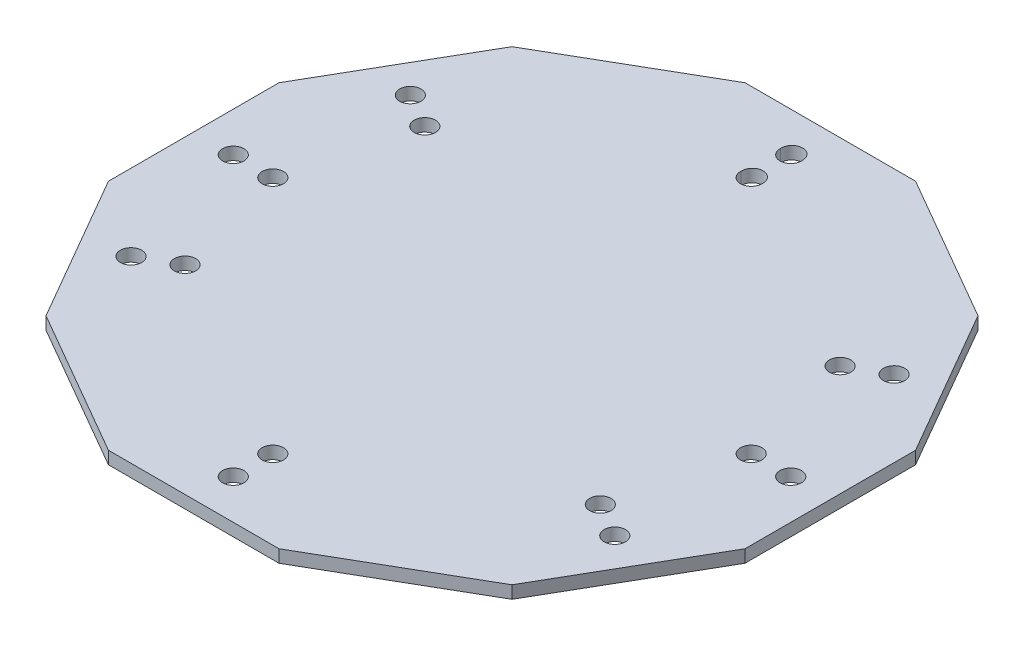
SolidWorks part; units mm, degrees
material "6063-T6"
ref_plane "Front Plane" through (0, 0, 0) normal (0, 0, 1) x (1, 0, 0)
ref_plane "Top Plane" through (0, 0, 0) normal (0, 1, 0) x (1, 0, 0)
ref_plane "Right Plane" through (0, 0, 0) normal (1, 0, 0) x (0, 0, -1)
sketch "Sketch2" plane through (0, 0, 0) normal (0, 1, 0) x (1, 0, 0)
  line L0 (-44.2539, 0) -> (44.2539, 0) construction
  line L1 (120.7407, 32.3524) -> (88.3883, 88.3883)
  line L2 (88.3883, 88.3883) -> (32.3524, 120.7407)
  line L3 (32.3524, 120.7407) -> (-32.3524, 120.7407)
  line L4 (-32.3524, 120.7407) -> (-88.3883, 88.3883)
  line L5 (-88.3883, 88.3883) -> (-120.7407, 32.3524)
  line L6 (-120.7407, 32.3524) -> (-120.7407, -32.3524)
  line L7 (-120.7407, -32.3524) -> (-88.3883, -88.3883)
  line L8 (-88.3883, -88.3883) -> (-32.3524, -120.7407)
  line L9 (-32.3524, -120.7407) -> (32.3524, -120.7407)
  line L10 (32.3524, -120.7407) -> (88.3883, -88.3883)
  line L11 (88.3883, -88.3883) -> (120.7407, -32.3524)
  line L12 (120.7407, -32.3524) -> (120.7407, 32.3524)
  circle A0 centre (0, 0) radius 125 construction
  dimension "D1" = 250
  dimension "D2" = 90
extrude "Boss-Extrude1" add sketch "Sketch2" along normal blind 4.78
sketch "Sketch3" plane through (0, 4.78, 0) normal (0, 1, 0) x (1, 0, 0)
  line L0 (-32.3524, -120.7407) -> (32.3524, -120.7407) construction
  circle A0 centre (-0.0024, -105.7407) radius 4.05
  circle A1 centre (-0.0024, -90.7407) radius 4.05
  point P6 (0, 0)
  point P7 (0, 0)
  point P9 (0, 0)
  dimension "D1" = 8.1
  dimension "D2" = 8.1
  dimension "D3" = 15
  dimension "D4" = 15
  dimension "D5" = 32.35
extrude "Cut-Extrude1" cut sketch "Sketch3" against normal up to surface (4.78 mm away) up to face at (0, 0, 0)
pattern_circular "CirPattern1" count 6 over 360 about axis through (0, 0, -0.2165) along (0, 1, 0) of "Cut-Extrude1"
pattern_circular "CirPattern3" count 4 over 360 about axis through (0, 0, 0.0029) along (0, 1, 0) of "Cut-Extrude1"
